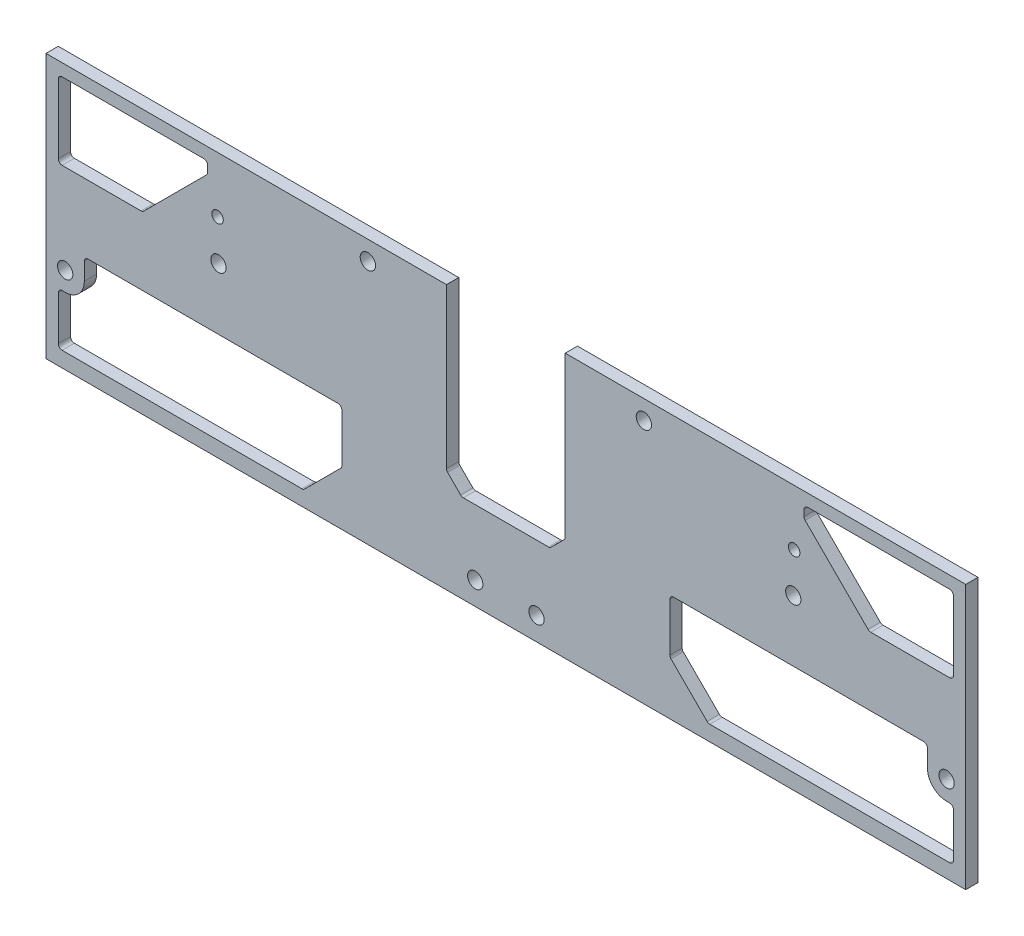
SolidWorks part; units mm, degrees
ref_plane "Front Plane" through (0, 0, 0) normal (0, 0, 1) x (1, 0, 0)
ref_plane "Top Plane" through (0, 0, 0) normal (0, 1, 0) x (1, 0, 0)
ref_plane "Right Plane" through (0, 0, 0) normal (1, 0, 0) x (0, 0, -1)
sketch "Sketch1" plane through (0, 0, 0) normal (0, 0, 1) x (1, 0, 0)
  line L0 (-6, -10) -> (-60, -10) construction
  line L1 (-60, -10) -> (60, -10)
  line L2 (-60, -10) -> (-60, 24.5)
  line L3 (-60, 24.5) -> (60, 24.5)
  line L4 (60, -10) -> (60, 24.5)
  line L5 (-60, -10) -> (-60, 24.5) construction
  line L6 (-39.15, 24.5) -> (-60, 24.5) construction
  point P4 (0, 24.5)
extrude "Boss-Extrude1" add sketch "Sketch1" along normal mid plane 1.6
sketch "Sketch2" plane through (0, 0, 0.8) normal (0, 0, 1) x (1, 0, 0)
  line L0 (-60, 24.5) -> (-60, -10) construction
  line L6 (-26.4, 4) -> (-26.4, -8) construction
  line L7 (-26.4, -8) -> (-58.4, -8)
  line L12 (-58.4, 22.9) -> (-38.9, 22.9)
  line L13 (0, 0) -> (0, 24.5) construction
  line L14 (60, 24.5) -> (-60, 24.5) construction
  line L25 (60, 24.5) -> (-60, 24.5) construction
  line L26 (7.746, 24.5) -> (-7.746, 24.5)
  line L27 (7.746, 24.5) -> (7.746, 3.5)
  line L28 (7.746, 3.5) -> (-7.746, 3.5) construction
  line L29 (-7.746, 24.5) -> (-7.746, 3.5)
  line L30 (37.6181, 17.705) -> (37.6181, 16.7398) construction
  line L33 (-58.4, 22.9) -> (-58.4, 12.9)
  line L34 (-58.4, 12.9) -> (-47.4, 12.9)
  line L35 (-38.9, 22.9) -> (-38.9, 21.4)
  line L37 (-47.4, 12.9) -> (-38.9, 21.4)
  line L38 (-57.5, -1.25) -> (-58.4, -1.25)
  line L39 (-58.4, -1.25) -> (-58.4, -8)
  line L40 (-55, 1.25) -> (-55, 4)
  line L41 (-55, 4) -> (-26.4, 4)
  line L42 (-60, -10) -> (60, -10) construction
  line L43 (-7.746, 3.5) -> (-5.756, 1.51)
  line L44 (-5.756, 1.51) -> (5.756, 1.51)
  line L45 (5.756, 1.51) -> (7.746, 3.5)
  line L46 (58.4, 22.9) -> (58.4, 12.9)
  line L55 (58.4, 12.9) -> (47.4, 12.9)
  line L56 (47.4, 12.9) -> (38.9, 21.4)
  line L57 (38.9, 22.9) -> (38.9, 21.4)
  line L58 (58.4, 22.9) -> (38.9, 22.9)
  line L65 (-26.4, 4) -> (-21.4, 4)
  line L66 (-21.4, 4) -> (-21.4, -3)
  line L67 (-21.4, -3) -> (-26.4, -8)
  line L69 (21.4, 4) -> (21.4, -3)
  line L70 (26.4, 4) -> (21.4, 4)
  line L71 (55, 4) -> (26.4, 4)
  line L72 (55, 1.25) -> (55, 4)
  line L73 (57.5, -1.25) -> (58.4, -1.25)
  line L74 (58.4, -1.25) -> (58.4, -8)
  line L75 (26.4, -8) -> (58.4, -8)
  line L76 (21.4, -3) -> (26.4, -8)
  circle A0 centre (-37.5, 12) radius 1
  circle A1 centre (-4, -7) radius 1
  circle A3 centre (37.5, 12) radius 1
  circle A4 centre (-57.5, 1.25) radius 1
  circle A6 centre (57.5, 1.25) radius 1
  arc A7 (-57.5, -1.25) -> (-55, 1.25) centre (-57.5, 1.25) ccw
  arc A10 (57.5, -1.25) -> (55, 1.25) centre (57.5, 1.25) cw
  circle A25 centre (-57.5, 1.25) radius 0.8 construction
  circle A26 centre (-37.5, 12) radius 0.8 construction
  circle A27 centre (37.5, 12) radius 1.8 construction
  circle A28 centre (4, -7) radius 1
  circle A29 centre (-4, -7) radius 0.8 construction
  circle A30 centre (4, -7) radius 1.8 construction
  circle A31 centre (-18.005, 22) radius 1
  circle A32 centre (18.005, 22) radius 1
  circle A33 centre (37.6181, 17.2224) radius 0.75
  circle A34 centre (-37.6181, 17.2224) radius 0.75
  point P24 (0, 3.5)
  point P28 (-58.4, 22.9)
  point P29 (-38.9, 12.9)
  dimension "D1" = 2
  dimension "D2" = 15.492
  dimension "D4" = 1.5
  dimension "D9" = 2.5
  dimension "D3" = 21
  dimension "D5" = 1.6
  dimension "D6" = 1.6
  dimension "D7" = 19.5
  dimension "D8" = 10
  dimension "D11" = 45
  dimension "D16" = 45
  dimension "D10" = 1.6
  dimension "D13" = 12
  dimension "D14" = 2
  dimension "D15" = 32
  dimension "D17" = 1.99
  dimension "D18" = 5
extrude "Cut-Extrude1" cut sketch "Sketch2" against normal through all both and the other way through all
fillet "Fillet1" radius 0.5
